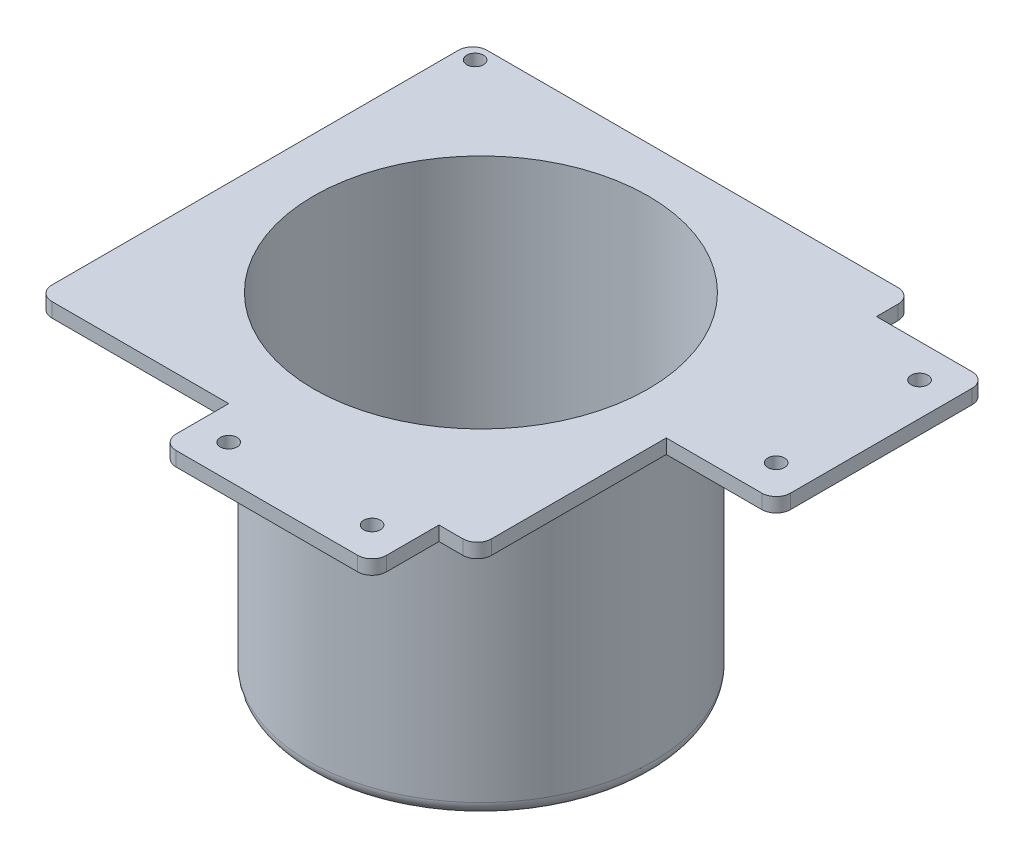
SolidWorks part; units mm, degrees
ref_plane "Plan de face" through (0, 0, 0) normal (0, 0, 1) x (1, 0, 0)
ref_plane "Plan de dessus" through (0, 0, 0) normal (0, 1, 0) x (1, 0, 0)
ref_plane "Plan de droite" through (0, 0, 0) normal (1, 0, 0) x (0, 0, -1)
sketch "Esquisse1" plane through (0, 0, 0) normal (0, 1, 0) x (1, 0, 0)
  line L0 (0, 91.06) -> (0, 0)
  line L1 (0, 91.06) -> (92, 91.06)
  line L2 (92, 91.06) -> (92, 83.56)
  line L3 (92, 83.56) -> (115, 83.56)
  line L4 (115, 83.56) -> (115, 39.56)
  line L5 (115, 39.56) -> (92, 39.56)
  line L6 (92, 39.56) -> (92, 0)
  line L8 (11.27, 87.06) -> (88, 87.06)
  line L9 (11.27, 87.06) -> (11.27, 73.06)
  line L10 (11.27, 73.06) -> (4.5, 73.06)
  line L11 (4.5, 73.06) -> (4.5, 6)
  line L12 (4.5, 6) -> (88, 6)
  line L13 (88, 6) -> (88, 87.06)
  line L14 (84, 0) -> (84, -14)
  line L15 (0, 0) -> (40, 0)
  line L16 (40, 0) -> (40, -14)
  line L17 (40, -14) -> (84, -14)
  line L18 (84, 0) -> (92, 0)
  circle A0 centre (108, 46.56) radius 1.75
  circle A1 centre (108, 76.56) radius 1.75
  circle A2 centre (3.5, 88.06) radius 1.75
  circle A3 centre (77, -7) radius 1.75
  circle A4 centre (47, -7) radius 1.75
  dimension "D6" = 91.06
  dimension "D3" = 4.5
  dimension "D4" = 92
  dimension "D8" = 44
  dimension "D9" = 81.06
extrude "Boss.-Extru.1" add sketch "Esquisse1" against normal blind 3
sketch "Esquisse2" plane through (0, 0, 0) normal (0, 1, 0) x (1, 0, 0)
  line L0 (11.27, 73.06) -> (4.5, 73.06)
  line L1 (4.5, 73.06) -> (4.5, 6)
  line L2 (4.5, 6) -> (88, 6)
  line L3 (88, 6) -> (88, 87.06)
  line L4 (88, 87.06) -> (11.27, 87.06)
  line L5 (11.27, 87.06) -> (11.27, 73.06)
  circle A0 centre (46.25, 46.53) radius 36
  dimension "D1" = 72
extrude "Boss.-Extru.4" add sketch "Esquisse2" against normal blind 0.5
sketch "Esquisse5" plane through (0, 0, 0) normal (0, 1, 0) x (1, 0, 0)
  circle A1 centre (46.25, 46.53) radius 35
  circle A2 centre (46.25, 46.53) radius 36
  dimension "D1" = 70
extrude "Boss.-Extru.6" add sketch "Esquisse5" against normal blind 68
sketch "Esquisse6" plane through (0, -68, 0) normal (0, -1, 0) x (1, 0, 0)
  circle A0 centre (46.25, -46.53) radius 36
extrude "Boss.-Extru.7" add sketch "Esquisse6" along normal blind 2
fillet "Congé7" radius 3 1 edges at (0, -1.5, -91.06)
fillet "Congé8" radius 3 1 edges at (40, -1.5, 14)
fillet "Congé9" radius 3 1 edges at (0, -1.5, 0)
fillet "Congé10" radius 3 1 edges at (92, -1.5, 0)
fillet "Congé11" radius 3 1 edges at (84, -1.5, 14)
fillet "Congé12" radius 3 1 edges at (115, -1.5, -39.56)
fillet "Congé13" radius 3 1 edges at (115, -1.5, -83.56)
fillet "Congé15" radius 3 1 edges at (92, -1.5, -91.06)
fillet "Congé16" radius 3 1 edges at (46.25, -70, -82.53)
sketch "Esquisse7" plane through (0, -0.5, 0) normal (0, -1, 0) x (1, 0, 0)
  line L0 (4.5, -6) -> (88, -6)
  line L1 (88, -6) -> (88, -87.06)
  line L2 (88, -87.06) -> (11.27, -87.06) construction
  line L3 (88, -6) -> (88, -87.06) construction
  line L4 (88, -87.06) -> (11.27, -87.06)
  line L5 (11.27, -87.06) -> (11.27, -73.06)
  line L6 (11.27, -73.06) -> (4.5, -73.06)
  line L7 (4.5, -73.06) -> (4.5, -6) construction
  line L8 (4.5, -73.06) -> (4.5, -6)
  circle A0 centre (46.25, -46.53) radius 36
extrude "Boss.-Extru.9" add sketch "Esquisse7" along normal blind 2.5
